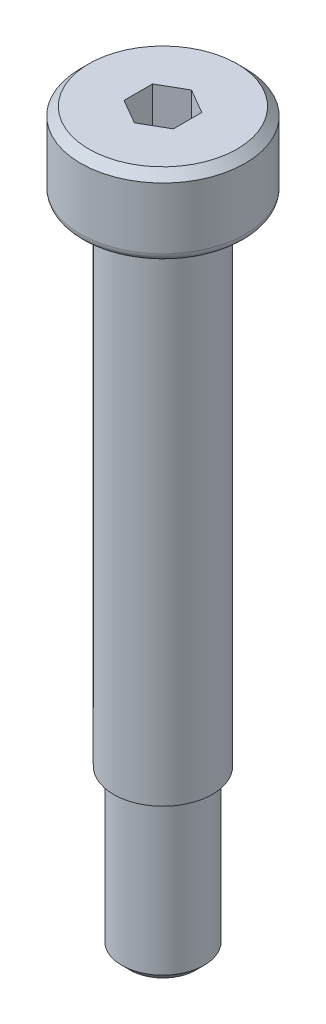
SolidWorks part; units mm, degrees
material "Plain Carbon Steel"
ref_plane "Front Plane" through (0, 0, 0) normal (0, 0, 1) x (1, 0, 0)
ref_plane "Top Plane" through (0, 0, 0) normal (0, 1, 0) x (1, 0, 0)
ref_plane "Right Plane" through (0, 0, 0) normal (1, 0, 0) x (0, 0, -1)
sketch "Sketch1" plane through (0, 0, 0) normal (0, 0, 1) x (1, 0, 0)
  line L0 (0, 0) -> (5, 0)
  line L1 (5, 0) -> (5, -4.73)
  line L2 (5, -4.73) -> (2.75, -4.73)
  line L3 (2.75, -4.73) -> (2.75, -5.23)
  line L4 (2.75, -5.23) -> (3, -5.23)
  line L5 (3, -5.23) -> (3, -34.73)
  line L6 (3, -34.73) -> (2.5, -34.73)
  line L7 (2.5, -34.73) -> (2.5, -44.48)
  line L8 (2.5, -44.48) -> (0, -44.48)
  line L9 (0, -44.48) -> (0, 0)
  line L10 (0, 5) -> (0, -49.48) construction
  dimension "D1" = 5
  dimension "D2" = 5
  dimension "D3" = 5
  dimension "D4" = 6
  dimension "D5" = 0.25
  dimension "D6" = 10
  dimension "D7" = 30
  dimension "D8" = 4.73
  dimension "D9" = 0.5
  dimension "D10" = 9.75
revolve "Revolve1" add sketch "Sketch1" angle 360 about L10
sketch "Sketch2" plane through (0, 0, 0) normal (0, 1, 0) x (1, 0, 0)
  line L1 (0, -1.7321) -> (1.5, -0.866)
  line L2 (1.5, -0.866) -> (1.5, 0.866)
  line L3 (1.5, 0.866) -> (0, 1.7321)
  line L4 (0, 1.7321) -> (-1.5, 0.866)
  line L5 (-1.5, 0.866) -> (-1.5, -0.866)
  line L6 (-1.5, -0.866) -> (0, -1.7321)
  circle A0 centre (0, 0) radius 1.5 construction
  dimension "D1" = 3
extrude "Cut-Extrude1" cut sketch "Sketch2" against normal blind 2.4
chamfer "Chamfer1" distance 0.5 angle 45 1 edges at (-5, 0, 0)
fillet "Fillet1" radius 0.5 1 edges at (-5, -4.73, 0)
chamfer "Chamfer2" distance 0.5 angle 45 1 edges at (-2.5, -44.48, 0)
